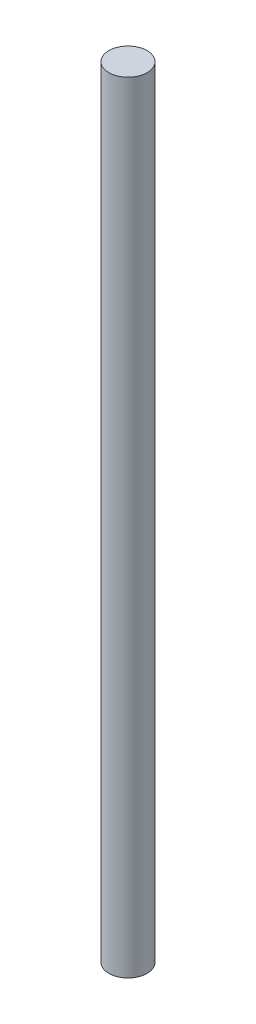
SolidWorks part; units mm, degrees
ref_plane "前视基准面" through (0, 0, 0) normal (0, 0, 1) x (1, 0, 0)
ref_plane "上视基准面" through (0, 0, 0) normal (0, 1, 0) x (1, 0, 0)
ref_plane "右视基准面" through (0, 0, 0) normal (1, 0, 0) x (0, 0, -1)
sketch "草图1" plane through (0, 0, 0) normal (0, 1, 0) x (1, 0, 0)
  circle A0 centre (0, 0) radius 1.5
  dimension "D1" = 3
extrude "凸台-拉伸1" add sketch "草图1" along normal blind 61.2
